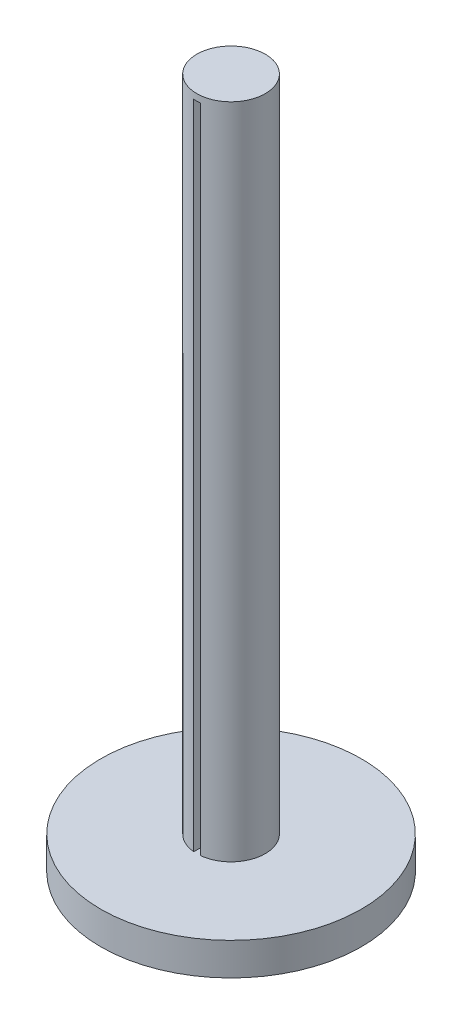
SolidWorks part; units mm, degrees
ref_plane "Plan de face" through (0, 0, 0) normal (0, 0, 1) x (1, 0, 0)
ref_plane "Plan de dessus" through (0, 0, 0) normal (0, 1, 0) x (1, 0, 0)
ref_plane "Plan de droite" through (0, 0, 0) normal (1, 0, 0) x (0, 0, -1)
sketch "Esquisse2" plane through (0, 0, 0) normal (0, 1, 0) x (1, 0, 0)
  circle A0 centre (0, 0) radius 52.5
  dimension "D1" = 105
extrude "Cylindre" add sketch "Esquisse2" along normal blind 1000
sketch "Esquisse3" plane through (0, 1000, 0) normal (0, 1, 0) x (1, 0, 0)
  line L0 (-52.5, 0) -> (52.5, 0)
  line L1 (0, 52.5) -> (0, -52.5)
  line L2 (-5, -29.5804) -> (-5, -52.5)
  line L3 (-5, -52.5) -> (5, -52.5)
  line L4 (5, -52.5) -> (5, -29.5804)
  line L5 (5, -29.5804) -> (-5, -29.5804)
  circle A0 centre (0, 0) radius 52.5 construction
  circle A1 centre (0, 0) radius 30
  circle A2 centre (0, 0) radius 52.5
  circle M1 centre (0, 0) radius 52.5
  dimension "D1" = 5
  dimension "D2" = 60
  dimension "D3" = 5
extrude "Fente" cut sketch "Esquisse3" against normal through all contours A1 L2 L1 M1 | A1 L1 L4 M1
sketch "Esquisse4" plane through (0, 1000, 0) normal (0, 1, 0) x (1, 0, 0)
  circle A0 centre (0, 0) radius 200
  dimension "D1" = 400
extrude "Socle" add sketch "Esquisse4" along normal blind 50
move or copy body "Corps-Déplacer/Copier1" bodies to move or copy 109 copy no rotation origin (0, 525, 0) rotation axis (0, 0, 1) rotation angle 180
sketch "Esquisse5" plane through (0, 1050, 0) normal (0, 1, 0) x (1, 0, 0)
  circle A0 centre (0, 0) radius 52.5
extrude "Boss.-Extru.4" add sketch "Esquisse5" along normal blind 10
